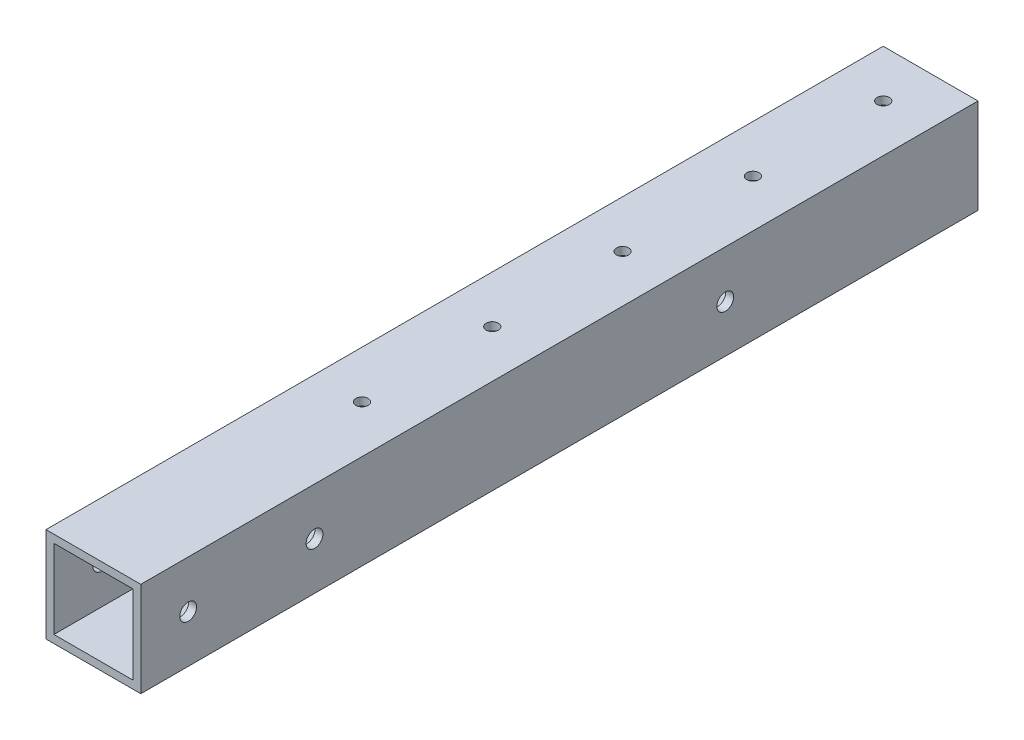
SolidWorks part; units mm, degrees
material "6061 Alloy"
ref_plane "Front Plane" through (0, 0, 0) normal (0, 0, 1) x (1, 0, 0)
ref_plane "Top Plane" through (0, 0, 0) normal (0, 1, 0) x (1, 0, 0)
ref_plane "Right Plane" through (0, 0, 0) normal (1, 0, 0) x (0, 0, -1)
sketch "Sketch1" plane through (0, 0, 0) normal (0, 0, 1) x (1, 0, 0)
  line L1 (-19.05, -19.05) -> (19.05, -19.05)
  line L2 (-19.05, -19.05) -> (-19.05, 19.05)
  line L3 (-19.05, 19.05) -> (19.05, 19.05)
  line L4 (19.05, -19.05) -> (19.05, 19.05)
  line L5 (-19.05, -19.05) -> (19.05, 19.05) construction
  line L6 (-19.05, 19.05) -> (19.05, -19.05) construction
  line L7 (-15.875, -15.875) -> (15.875, -15.875)
  line L8 (-15.875, -15.875) -> (-15.875, 15.875)
  line L9 (-15.875, 15.875) -> (15.875, 15.875)
  line L10 (15.875, -15.875) -> (15.875, 15.875)
  line L11 (-15.875, -15.875) -> (15.875, 15.875) construction
  line L12 (-15.875, 15.875) -> (15.875, -15.875) construction
  point P0 (0, 0)
  point P6 (0, 0)
  dimension "D1" = 3.175
  dimension "D2" = 3.175
  dimension "D3" = 38.1
  dimension "D4" = 38.1
extrude "Boss-Extrude1" add sketch "Sketch1" along normal blind 165.1 and the other way blind 171.45
hole_wizard "1/4 Clearance Hole1" positions "Sketch3" profile "Sketch4" hole size "1/4" standard "ANSI Inch" end condition through all
sketch "Sketch3" plane through (19.05, 0, 0) normal (1, 0, 0) x (0, 0, -1)
  line L0 (-165.1, -19.05) -> (-165.1, 19.05) construction
  line L1 (-165.1, 19.05) -> (-165.1, -19.05) construction
  line L2 (171.45, 19.05) -> (-165.1, 19.05) construction
  line L3 (171.45, -19.05) -> (-165.1, -19.05) construction
  line L4 (-165.1, 0) -> (171.45, 0) construction
  line L5 (171.45, -19.05) -> (171.45, 19.05) construction
  point P3 (-146.05, 0)
  point P9 (69.85, 0)
  point P34 (-95.25, 0)
  dimension "D1" = 69.85
  dimension "D2" = 234.95
  dimension "D3" = 19.05
sketch "Sketch4" plane through (19.05, 0, 146.05) normal (0, 1, 0) x (0, 0, -1)
  line L0 (0, 0) -> (0, 38.1)
  line L1 (0, 38.1) -> (3.3782, 38.1)
  line L2 (3.3782, 38.1) -> (3.3782, 0)
  line L5 (3.3782, 0) -> (0, 0)
  line L11 (0, -6.35) -> (0, 107.95) construction
  dimension "Thru Hole Dia." = 6.7564
  dimension "Thru Hole Depth" = 38.1
hole_wizard "#10 (0.1935) Diameter Hole1" positions "Sketch5" profile "Sketch6" hole size "#10" standard "ANSI Inch" end condition through all
sketch "Sketch5" plane through (0, 19.05, 0) normal (0, 1, 0) x (1, 0, 0)
  line L0 (19.05, -76.2) -> (-19.05, -76.2) construction
  line L1 (19.05, 171.45) -> (19.05, -165.1) construction
  line L2 (-19.05, 171.45) -> (-19.05, -165.1) construction
  line L3 (19.05, 171.45) -> (-19.05, 171.45) construction
  line L4 (19.05, -76.2) -> (19.05, 171.45) construction
  line L5 (19.05, 47.625) -> (-19.05, 47.625) construction
  point P10 (0, 152.4)
  point P28 (0, 100.0125)
  point P29 (0, 47.625)
  point P30 (0, -4.7625)
  point P31 (0, -57.15)
  dimension "D1" = 247.65
  dimension "D3" = 19.05
  dimension "D2" = 5
sketch "Sketch6" plane through (0, 19.05, 57.15) normal (1, 0, 0) x (0, 0, 1)
  line L0 (0, 0) -> (0, 38.1)
  line L1 (0, 38.1) -> (2.4574, 38.1)
  line L2 (2.4574, 38.1) -> (2.4574, 0)
  line L5 (2.4574, 0) -> (0, 0)
  line L11 (0, -6.35) -> (0, 107.95) construction
  dimension "Thru Hole Dia." = 4.9149
  dimension "Thru Hole Depth" = 38.1
